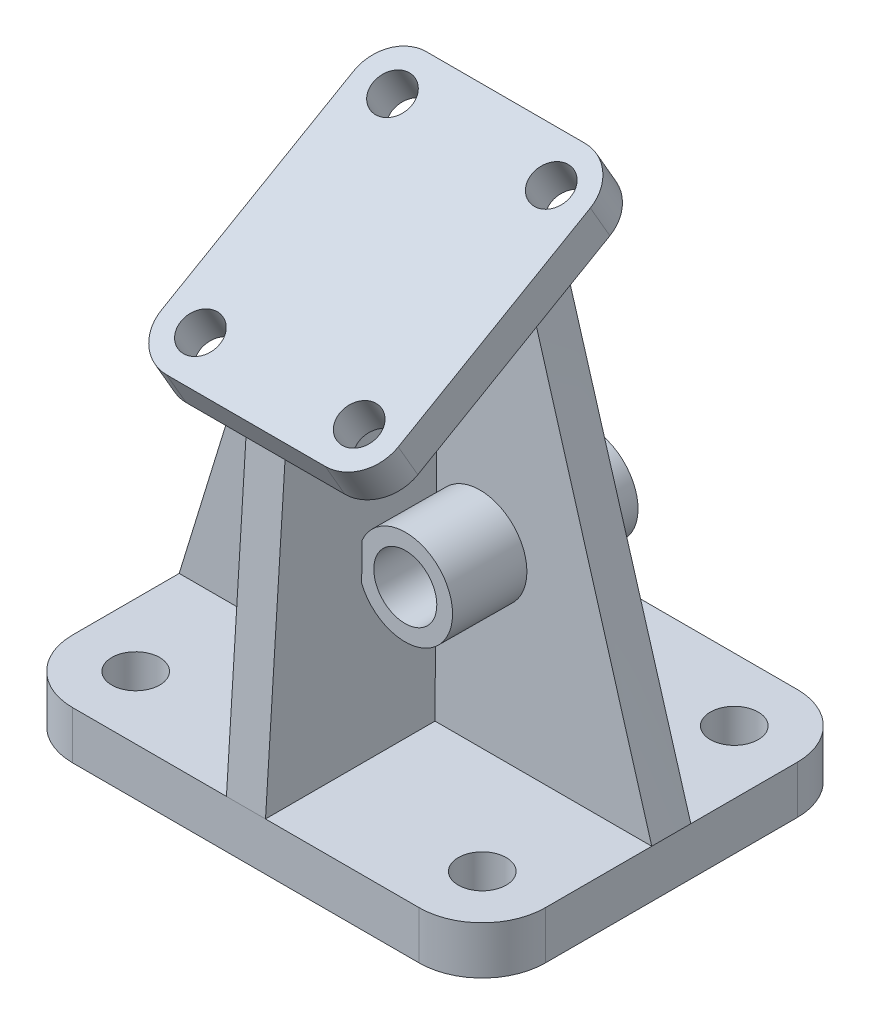
SolidWorks part; units mm, degrees
ref_plane "Front Plane" through (0, 0, 0) normal (0, 0, 1) x (1, 0, 0)
ref_plane "Top Plane" through (0, 0, 0) normal (0, 1, 0) x (1, 0, 0)
ref_plane "Right Plane" through (0, 0, 0) normal (1, 0, 0) x (0, 0, -1)
sketch "Sketch7" plane through (0, 0, 0) normal (0, 1, 0) x (1, 0, 0)
  line L0 (-47.625, 0) -> (47.625, 0) construction
  line L1 (-34.925, 38.1) -> (34.925, 38.1)
  line L2 (-47.625, 25.4) -> (-47.625, -25.4)
  line L3 (-34.925, -38.1) -> (34.925, -38.1)
  line L4 (47.625, 25.4) -> (47.625, -25.4)
  line L5 (-47.625, 38.1) -> (47.625, -38.1) construction
  line L6 (-47.625, -38.1) -> (47.625, 38.1) construction
  line L7 (0, 38.1) -> (0, -38.1) construction
  arc A0 (34.925, 38.1) -> (47.625, 25.4) centre (34.925, 25.4) cw
  arc A1 (-47.625, -25.4) -> (-34.925, -38.1) centre (-34.925, -25.4) ccw
  arc A2 (-34.925, 38.1) -> (-47.625, 25.4) centre (-34.925, 25.4) ccw
  arc A3 (34.925, -38.1) -> (47.625, -25.4) centre (34.925, -25.4) ccw
  circle A4 centre (-34.925, 25.4) radius 4.826
  circle A5 centre (34.925, 25.4) radius 4.826
  circle A6 centre (34.925, -25.4) radius 4.826
  circle A7 centre (-34.925, -25.4) radius 4.826
  point P0 (0, 0)
  dimension "D3" = 12.7
  dimension "D4" = 9.652
  dimension "D1" = 76.2
  dimension "D2" = 95.25
extrude "Boss-Extrude2" add sketch "Sketch7" against normal blind 9.652
sketch "Sketch10" plane through (0, 0, 0) normal (1, 0, 0) x (0, 0, -1)
  line L0 (-38.1, 0) -> (-38.1, 67.564) construction
  line L1 (-38.1, 67.564) -> (14.253, 97.79) construction
  dimension "D1" = 67.564
  dimension "D2" = 120
  dimension "D3" = 60.452
ref_plane "Plane1" through (0, 67.1708, 38.7811) normal (0, -0.866, -0.5) x (0, 0.5, -0.866)
sketch "Sketch11" plane through (0, 67.1708, 38.7811) normal (0, -0.866, -0.5) x (0, 0.5, -0.866)
  line L0 (31.0124, -23.876) -> (31.0124, 23.876) construction
  line L1 (53.3644, -23.876) -> (8.6604, -23.876)
  line L2 (61.2384, -16.002) -> (61.2384, 16.002)
  line L3 (53.3644, 23.876) -> (8.6604, 23.876)
  line L4 (0.7864, -16.002) -> (0.7864, 16.002)
  line L5 (61.2384, -23.876) -> (0.7864, 23.876) construction
  line L6 (61.2384, 23.876) -> (0.7864, -23.876) construction
  line L7 (0.7864, 0) -> (61.2384, 0) construction
  arc A0 (8.6604, -23.876) -> (0.7864, -16.002) centre (8.6604, -16.002) cw
  arc A1 (61.2384, 16.002) -> (53.3644, 23.876) centre (53.3644, 16.002) ccw
  arc A2 (53.3644, -23.876) -> (61.2384, -16.002) centre (53.3644, -16.002) ccw
  arc A3 (8.6604, 23.876) -> (0.7864, 16.002) centre (8.6604, 16.002) ccw
  circle A4 centre (53.3644, -16.002) radius 3.937
  circle A5 centre (8.6604, -16.002) radius 3.937
  circle A6 centre (53.3644, 16.002) radius 3.937
  circle A7 centre (8.6604, 16.002) radius 3.937
  point P0 (31.0124, 0)
  dimension "D3" = 7.874
  dimension "D4" = 7.874
  dimension "D1" = 60.452
  dimension "D2" = 47.752
extrude "Boss-Extrude3" add sketch "Sketch11" along normal blind 7.874 separate body
sketch "Sketch12" plane through (0, 0, 0) normal (0, 1, 0) x (1, 0, 0)
  line L0 (47.625, -25.4) -> (47.625, 25.4) construction
  line L1 (-47.625, 3.937) -> (47.625, 3.937)
  line L2 (-47.625, 3.937) -> (-47.625, -3.937)
  line L3 (-47.625, -3.937) -> (47.625, -3.937)
  line L4 (47.625, 3.937) -> (47.625, -3.937)
  line L5 (-47.625, 3.937) -> (47.625, -3.937) construction
  line L6 (-47.625, -3.937) -> (47.625, 3.937) construction
  line L7 (-34.925, -38.1) -> (34.925, -38.1) construction
  point P0 (0, 0)
  point P7 (47.625, 0)
  dimension "D1" = 7.874
  dimension "D2" = 38.1
sketch "Sketch13" plane through (0, 0, 0) normal (0, 0, 1) x (1, 0, 0)
  line L0 (47.625, 0) -> (23.876, 80.4689)
  point P3 (0, 0)
sketch "Sketch15" plane through (0, 60.3517, 34.8441) normal (0, -0.866, -0.5) x (1, 0, 0)
  line L0 (-23.876, -8.6604) -> (-23.876, -53.3644) construction
  line L1 (23.876, -36.2975) -> (-23.876, -36.2975)
  line L2 (23.876, -36.2975) -> (23.876, -44.1715)
  line L3 (23.876, -44.1715) -> (-23.876, -44.1715)
  line L4 (-23.876, -36.2975) -> (-23.876, -44.1715)
  line L5 (23.876, -36.2975) -> (-23.876, -44.1715) construction
  line L6 (23.876, -44.1715) -> (-23.876, -36.2975) construction
  point P0 (-42.102, -33.2921)
  point P11 (0, 0)
  dimension "D1" = 7.874
loft "Loft1" add profiles "Sketch15", "Sketch12"
sketch "Sketch16" plane through (0, 0, 0) normal (1, 0, 0) x (0, 0, -1)
  line L0 (-38.1, 0) -> (-34.163, 60.7449)
rib "Rib1" sketch "Sketch16" sketch "Sketch16" thickness 7.874 extrusion direction parallel to sketch draft on no parameters "D1"=7.874
sketch "Sketch17" plane through (0, 0.0265, 3.9368) normal (0, 0.0067, 1) x (1, 0, 0)
  line L0 (3.937, -0.0265) -> (47.625, -0.0265) construction
  circle A0 centre (12.7, 35.0255) radius 9.525
  circle A1 centre (12.7, 35.0255) radius 6.35
  dimension "D1" = 19.05
  dimension "D4" = 12.7
  dimension "D2" = 35.052
  dimension "D3" = 12.7
extrude "Boss-Extrude4" add sketch "Sketch17" along normal blind 14.986
sketch "Sketch18" plane through (0, 0.0252, -3.9368) normal (0, 0.0064, -1) x (-1, 0, 0)
  line L0 (-34.925, -0.2438) -> (34.925, -0.2438) construction
  circle A0 centre (-12.7, 34.8082) radius 9.525
  circle A1 centre (-12.7, 34.8082) radius 6.35
  dimension "D3" = 19.05
  dimension "D4" = 12.7
  dimension "D1" = 35.052
  dimension "D2" = 12.7
extrude "Boss-Extrude5" add sketch "Sketch18" along normal blind 14.986
sketch "Sketch19" plane through (0, 0, 38.1) normal (0, 0, 1) x (1, 0, 0)
  line L1 (-34.925, -8.128) -> (34.925, -8.128)
  line L2 (-34.925, -8.128) -> (-34.925, -9.652)
  line L3 (-34.925, -9.652) -> (34.925, -9.652)
  line L4 (34.925, -8.128) -> (34.925, -9.652)
  line L5 (-34.925, -8.128) -> (34.925, -9.652) construction
  line L6 (-34.925, -9.652) -> (34.925, -8.128) construction
  point P0 (0, -8.89)
  dimension "D1" = 69.85
  dimension "D2" = 1.524
